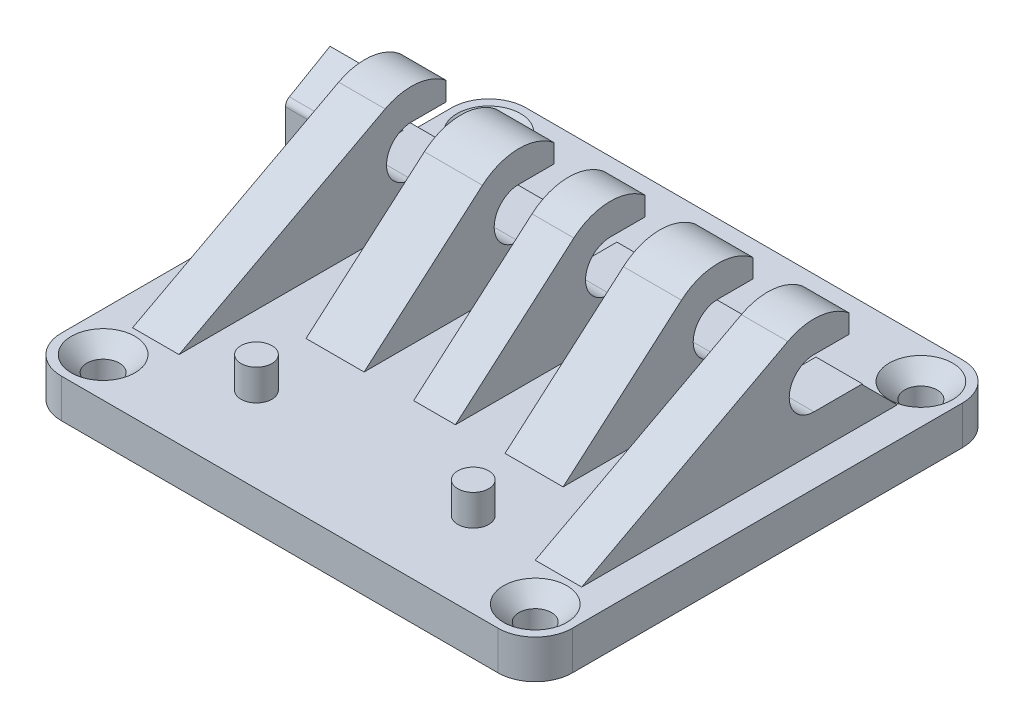
SolidWorks part; units mm, degrees
other "Markup1"
sketch "Sketch13" plane through (0, 20, 0) normal (-0.5335, 0.7333, 0.4215) x (0.8394, 0.3978, 0.3704)
sketch "Sketch14" plane through (0, 20, 0) normal (-0.5335, 0.7333, 0.4215) x (0.8394, 0.3978, 0.3704)
ref_plane "Front Plane" through (0, 0, 0) normal (0, 0, 1) x (1, 0, 0)
ref_plane "Top Plane" through (0, 0, 0) normal (0, 1, 0) x (1, 0, 0)
ref_plane "Right Plane" through (0, 0, 0) normal (1, 0, 0) x (0, 0, -1)
sketch "Sketch4" plane through (0, 0, 0) normal (0, 1, 0) x (1, 0, 0)
  line L0 (33, 60) -> (33, 0) construction
  line L1 (0, 0) -> (66, 0)
  line L2 (0, 0) -> (0, 60)
  line L3 (0, 60) -> (66, 60)
  line L4 (66, 0) -> (66, 60)
  line L6 (30.3, 20) -> (35.7, 20)
  line L7 (30.3, 20) -> (30.3, 60)
  line L8 (30.3, 60) -> (35.7, 60)
  line L9 (35.7, 20) -> (35.7, 60)
  line L10 (30.3, 20) -> (35.7, 60) construction
  line L11 (30.3, 60) -> (35.7, 20) construction
  line L12 (35.7, 60) -> (42.1, 60)
  line L13 (35.7, 60) -> (35.7, 20)
  line L14 (35.7, 20) -> (42.1, 20)
  line L15 (42.1, 60) -> (42.1, 20)
  line L16 (42.1, 20) -> (49.6, 20)
  line L17 (42.1, 20) -> (42.1, 60)
  line L18 (42.1, 60) -> (49.6, 60)
  line L19 (49.6, 20) -> (49.6, 60)
  line L20 (49.6, 60) -> (56, 60)
  line L21 (49.6, 60) -> (49.6, 20)
  line L22 (49.6, 20) -> (56, 20)
  line L23 (56, 60) -> (56, 20)
  line L24 (56, 50) -> (62, 50)
  line L25 (56, 50) -> (56, 10)
  line L26 (56, 10) -> (62, 10)
  line L27 (62, 50) -> (62, 10)
  point P7 (33, 40)
  point P22 (52.8, 20)
  dimension "D1" = 6
  dimension "D2" = 6.4
  dimension "D3" = 7.5
  dimension "D4" = 5.4
  dimension "D5" = 10
  dimension "D6" = 10
  dimension "D7" = 20
  dimension "D8" = 40
  dimension "D9" = 10
  dimension "D10" = 6.4
  dimension "D11" = 66
extrude "Boss-Extrude4" add sketch "Sketch4" along normal blind 5 contours L24 L27 L26 L25 L22 L16 L14 L6 L7 L3 L2 L1 L4 L23 | L15 L3 L9 L14 | L6 L9 L3 L7 | L16 L19 L3 L15 | L23 L3 L19 L22 | L27 L24 L23 L25 L26
sketch "Sketch6" plane through (0, 5, 0) normal (0, 1, 0) x (1, 0, 0)
  line L0 (42.1, 60) -> (49.6, 60) construction
  line L1 (49.6, 20) -> (49.6, 60) construction
  line L2 (49.6, 60) -> (56, 60) construction
  line L3 (56, 60) -> (56, 20) construction
  line L4 (66, 0) -> (66, 60)
  line L5 (66, 60) -> (0, 60)
  line L6 (0, 60) -> (0, 0)
  line L7 (0, 0) -> (66, 0)
  line L8 (66, 0) -> (66, 60)
  line L9 (66, 60) -> (0, 60)
  line L10 (0, 60) -> (0, 0)
  line L11 (0, 0) -> (66, 0)
  line L12 (49.6, 20) -> (56, 20) construction
  line L13 (49.6, 60) -> (49.6, 20) construction
  line L14 (42.1, 20) -> (49.6, 20) construction
  line L15 (35.7, 20) -> (42.1, 20) construction
  line L16 (42.1, 60) -> (42.1, 20) construction
  line L17 (42.1, 20) -> (42.1, 60) construction
  line L18 (35.7, 60) -> (42.1, 60) construction
  line L19 (30.3, 20) -> (35.7, 20) construction
  line L20 (30.3, 20) -> (30.3, 60) construction
  line L21 (30.3, 60) -> (35.7, 60) construction
  line L22 (35.7, 20) -> (35.7, 60) construction
  line L23 (35.7, 60) -> (35.7, 20) construction
  line L24 (0, 0) -> (66, 0) construction
  line L25 (66, 0) -> (66, 60) construction
  line L26 (0, 60) -> (66, 60) construction
  line L27 (0, 0) -> (0, 60) construction
  line L28 (56, 50) -> (62, 50) construction
  line L29 (62, 50) -> (62, 10) construction
  line L30 (56, 10) -> (62, 10) construction
  line L31 (56, 50) -> (56, 10) construction
  line L32 (42.1, 60) -> (49.6, 60)
  line L33 (49.6, 20) -> (49.6, 60)
  line L34 (49.6, 60) -> (56, 60)
  line L35 (56, 60) -> (56, 20)
  line L36 (49.6, 20) -> (56, 20)
  line L37 (49.6, 60) -> (49.6, 20)
  line L38 (42.1, 20) -> (49.6, 20)
  line L39 (35.7, 20) -> (42.1, 20)
  line L40 (42.1, 60) -> (42.1, 20)
  line L41 (42.1, 20) -> (42.1, 60)
  line L42 (35.7, 60) -> (42.1, 60)
  line L43 (30.3, 20) -> (35.7, 20)
  line L44 (30.3, 20) -> (30.3, 60)
  line L45 (30.3, 60) -> (35.7, 60)
  line L46 (35.7, 20) -> (35.7, 60)
  line L47 (35.7, 60) -> (35.7, 20)
  line L48 (0, 0) -> (66, 0)
  line L49 (66, 0) -> (66, 60)
  line L50 (0, 60) -> (66, 60)
  line L51 (0, 0) -> (0, 60)
  line L52 (56, 50) -> (62, 50)
  line L53 (62, 50) -> (62, 10)
  line L54 (56, 10) -> (62, 10)
  line L55 (56, 50) -> (56, 10)
  dimension "D1" = 0
extrude "Boss-Extrude5" add sketch "Sketch6" along normal blind 15 contours L43 L46 L9 L44 | L9 L40 L38 L33 | L35 L55 L54 L53 L52
sketch "Sketch7" plane through (30.3, 0, 0) normal (-1, 0, 0) x (0, 0, 1)
  line L0 (-40, 20) -> (-40, 5) construction
  line L1 (-20, 20) -> (-60, 20) construction
  line L2 (-20, 5) -> (-60, 5) construction
  circle A0 centre (-40, 12.8) radius 3.2
  point P8 (-40, 16)
  dimension "D1" = 6.4
  dimension "D2" = 4
extrude "Cut-Extrude2" cut sketch "Sketch7" against normal through all
sketch "Sketch8" plane through (30.3, 0, 0) normal (-1, 0, 0) x (0, 0, 1)
  line L0 (-20, 5) -> (-35.2856, 18.2419)
  line L1 (-40, 21) -> (-40, 5) construction
  line L2 (-60, 5) -> (-44.7144, 18.2419)
  line L4 (-60, 5) -> (-20, 5)
  line L5 (-20, 5) -> (-20, 20)
  line L6 (-20, 20) -> (-60, 20)
  line L7 (-60, 20) -> (-60, 5)
  line L8 (-60, 5) -> (-20, 5)
  line L9 (-20, 5) -> (-20, 20)
  line L10 (-20, 20) -> (-60, 20)
  line L11 (-60, 20) -> (-60, 5)
  circle A0 centre (-40, 12.8) radius 3.2 construction
  circle A1 centre (-40, 12.8) radius 3.2
  arc A2 (-44.7144, 18.2419) -> (-35.2856, 18.2419) centre (-40, 12.8) cw
  line M10 (-20, 5) -> (-20, 20)
  line M11 (-20, 20) -> (-60, 20)
  line M12 (-60, 20) -> (-60, 5)
  dimension "D1" = 0
extrude "Cut-Extrude3" cut sketch "Sketch8" against normal up to surface (19.3 mm away) contours L2 A2 L10 M12 | A2 L0 M11 M10 up to face at (49.6, 12.8, -36.8)
sketch "Sketch9" plane through (62, 0, 0) normal (1, 0, 0) x (0, 0, -1)
  line L0 (46.8685, 14.9596) -> (50, 5)
  line L1 (10, 5) -> (36.6192, 19.1569)
  line L4 (10, 5) -> (50, 5)
  line L5 (50, 5) -> (50, 20)
  line L6 (50, 20) -> (10, 20)
  line L7 (10, 20) -> (10, 5)
  line L8 (10, 5) -> (50, 5)
  line L9 (50, 5) -> (50, 20)
  line L10 (50, 20) -> (10, 20)
  line L11 (10, 20) -> (10, 5)
  circle A0 centre (40, 12.8) radius 3.2 construction
  circle A1 centre (40, 12.8) radius 3.2
  arc A2 (40, 20) -> (46.8685, 14.9596) centre (40, 12.8) cw
  arc A3 (40, 20) -> (36.6192, 19.1569) centre (40, 12.8) ccw
  line M9 (50, 5) -> (50, 20)
  line M10 (50, 20) -> (10, 20)
  line M11 (10, 20) -> (10, 5)
  dimension "D1" = 0
extrude "Cut-Extrude4" cut sketch "Sketch9" against normal up to next contours A3 L10 L1 M11 | A2 L0 M10 M9
ref_plane "Plane1" through (33, 0, 0) normal (-1, 0, 0) x (0, 0, 1)
mirror "Mirror1" about plane through (33, 0, 0) normal (-1, 0, 0) of "Cut-Extrude4", "Cut-Extrude3", "Cut-Extrude2", "Boss-Extrude5"
sketch "Sketch10" plane through (0, 5, 0) normal (0, 1, 0) x (1, 0, 0)
  line L0 (33, 60) -> (33, 0) construction
  line L1 (60.9, 5.1) -> (5.1, 5.1) construction
  line L2 (60.9, 5.1) -> (60.9, 54.9) construction
  line L3 (60.9, 54.9) -> (5.1, 54.9) construction
  line L4 (5.1, 5.1) -> (5.1, 54.9) construction
  line L5 (60.9, 5.1) -> (5.1, 54.9) construction
  line L6 (60.9, 54.9) -> (5.1, 5.1) construction
  line L9 (0, 60) -> (66, 60) construction
  line L10 (0, 0) -> (0, 60) construction
  circle A0 centre (5.1, 54.9) radius 2.1
  circle A1 centre (60.9, 54.9) radius 2.1
  circle A2 centre (60.9, 5.1) radius 2.1
  circle A3 centre (5.1, 5.1) radius 2.1
  point P0 (33, 30)
  point P9 (5.1, 57)
  point P10 (3, 54.9)
  dimension "D3" = 4.2
  dimension "D1" = 3
  dimension "D2" = 3
extrude "Cut-Extrude5" cut sketch "Sketch10" against normal up to next
chamfer "Chamfer1" distance 2 angle 45 4 edges at (5.1, 5, -3) (60.9, 5, -3) (60.9, 5, -52.8) (5.1, 5, -52.8)
fillet "Fillet1" radius 4.8 4 edges at (66, 2.5, 0) (0, 2.5, 0) (66, 2.5, -60) (0, 2.5, -60)
sketch "Sketch11" plane through (0, 5, 0) normal (0, 1, 0) x (1, 0, 0)
  line L1 (35.7, 36.8) -> (35.7, 43.2) construction
  line L2 (35.7, 36.8) -> (35.7, 43.2)
  line L3 (33, 11) -> (33, -11) construction
  circle A0 centre (47, 11) radius 2
  circle A1 centre (19, 11) radius 2
  point P4 (35.7, 40)
  dimension "D1" = 4
  dimension "D3" = 28
  dimension "D2" = 29
extrude "Boss-Extrude6" add sketch "Sketch11" along normal blind 4 contours A1 | A0
sketch "Sketch12" plane through (4, 0, 0) normal (-1, 0, 0) x (0, 0, 1)
  line L0 (-45.25, 15.8311) -> (-46.25, 15.8311)
  line L1 (-34.75, 15.8311) -> (-40, 18.8622)
  line L2 (-40, 18.8622) -> (-45.25, 15.8311)
  line L3 (-45.25, 15.8311) -> (-45.25, 9.7689)
  line L4 (-45.25, 9.7689) -> (-40, 6.7378)
  line L5 (-40, 6.7378) -> (-34.75, 9.7689)
  line L6 (-34.75, 9.7689) -> (-34.75, 15.8311)
  line L7 (-46.25, 15.8311) -> (-46.25, 5)
  line L8 (-50, 5) -> (-10, 5) construction
  line L9 (-34.75, 15.8311) -> (-33.75, 15.8311)
  line L10 (-33.75, 15.8311) -> (-33.75, 5)
  line L11 (-46.25, 5) -> (-33.75, 5)
  line L12 (-46.25, 15.8311) -> (-45.25, 15.8311)
  line L13 (-34.75, 15.8311) -> (-33.75, 15.8311)
  line L14 (-40, 18.8622) -> (-34.75, 15.8311)
  line L15 (-40, 18.8622) -> (-39.5, 19.7282)
  line L16 (-34.75, 15.8311) -> (-34.25, 16.6971)
  line L17 (-39.5, 19.7282) -> (-34.25, 16.6971)
  line L18 (-46.25, 9.6) -> (-44.9574, 9.6)
  line L19 (-40, 9.6) -> (-54.6901, 9.6) construction
  line L20 (-44.7144, 18.2419) -> (-60, 5) construction
  circle A0 centre (-40, 12.8) radius 3.2 construction
  circle A1 centre (-40, 12.8) radius 3.2
  circle A2 centre (-40, 12.8) radius 5.25 construction
  arc A3 (-34.25, 16.6971) -> (-33.75, 15.8311) centre (-34.75, 15.8311) cw
  line M12 (-50, 5) -> (-10, 5)
  dimension "D1" = 10.5
  dimension "D2" = 1
extrude "Boss-Extrude7" add sketch "Sketch12" along normal up to surface (4 mm away) contours L10 L9 L6 L5 L4 L3 L0 L7 M12 | A3 L16 L9 | L17 L15 L1 L16
sketch "Sketch15" plane through (4, 0, 0) normal (-1, 0, 0) x (0, 0, 1)
  line L0 (-40, 16) -> (-47.3023, 16)
  line L1 (-40, 9.6) -> (-54.6901, 9.6)
  line L2 (-44.5, 16) -> (-44.5, 18.4205)
  line L3 (-20, 5) -> (-35.2856, 18.2419)
  line L4 (-44.7144, 18.2419) -> (-60, 5)
  line L5 (-60, 5) -> (-20, 5)
  line L6 (-20, 5) -> (-35.2856, 18.2419)
  line L7 (-44.7144, 18.2419) -> (-60, 5)
  line L8 (-60, 5) -> (-20, 5)
  line L22 (-55.2, 0) -> (-4.8, 0)
  line L23 (-4.8, 0) -> (-4.8, 5)
  line L24 (-4.8, 5) -> (-33.75, 5)
  line L25 (-33.75, 5) -> (-33.75, 15.8311)
  line L26 (-34.25, 16.6971) -> (-39.5, 19.7282)
  line L27 (-39.5, 19.7282) -> (-40, 18.8622)
  line L28 (-40, 18.8622) -> (-34.75, 15.8311)
  line L29 (-34.75, 15.8311) -> (-34.75, 9.7689)
  line L30 (-34.75, 9.7689) -> (-40, 6.7378)
  line L31 (-40, 6.7378) -> (-44.9574, 9.6)
  line L32 (-44.9574, 9.6) -> (-46.25, 9.6)
  line L33 (-46.25, 9.6) -> (-46.25, 5)
  line L34 (-46.25, 5) -> (-55.2, 5)
  line L35 (-55.2, 5) -> (-55.2, 0)
  line L36 (-55.2, 0) -> (-4.8, 0)
  line L37 (-4.8, 0) -> (-4.8, 5)
  line L38 (-4.8, 5) -> (-33.75, 5)
  line L39 (-33.75, 5) -> (-33.75, 15.8311)
  line L40 (-34.25, 16.6971) -> (-39.5, 19.7282)
  line L41 (-39.5, 19.7282) -> (-40, 18.8622)
  line L42 (-40, 18.8622) -> (-34.75, 15.8311)
  line L43 (-34.75, 15.8311) -> (-34.75, 9.7689)
  line L44 (-34.75, 9.7689) -> (-40, 6.7378)
  line L45 (-40, 6.7378) -> (-44.9574, 9.6)
  line L46 (-44.9574, 9.6) -> (-46.25, 9.6)
  line L47 (-46.25, 9.6) -> (-46.25, 5)
  line L48 (-46.25, 5) -> (-55.2, 5)
  line L49 (-55.2, 5) -> (-55.2, 0)
  circle A0 centre (-40, 12.8) radius 3.2 construction
  circle A1 centre (-40, 12.8) radius 3.2
  arc A3 (-35.2856, 18.2419) -> (-44.7144, 18.2419) centre (-40, 12.8) ccw
  arc A4 (-35.2856, 18.2419) -> (-44.7144, 18.2419) centre (-40, 12.8) ccw
  arc A5 (-33.75, 15.8311) -> (-34.25, 16.6971) centre (-34.75, 15.8311) ccw
  arc A6 (-33.75, 15.8311) -> (-34.25, 16.6971) centre (-34.75, 15.8311) ccw
  arc M10 (-36.6192, 19.1569) -> (-46.8685, 14.9596) centre (-40, 12.8) ccw
  line M11 (-46.8685, 14.9596) -> (-50, 5)
  line M12 (-50, 5) -> (-46.25, 5)
  line M13 (-46.25, 5) -> (-46.25, 9.6)
  line M14 (-46.25, 9.6) -> (-44.9574, 9.6)
  circle M21 centre (-40, 12.8) radius 3.2
  dimension "D3" = 4.5
  dimension "D1" = 0
  dimension "D2" = 0
extrude "Cut-Extrude6" cut sketch "Sketch15" against normal through all contours L1 L0 M21 M10 M11 M14 | L0 L7 L1 M11 M10 | L7 L8 L1 M11 | L1 M13 M11 M12 | L0 L2 M10 | L7 L0 M10
chamfer "Chamfer2" distance 4.5 angle 45 5 edges at (5, 5, -46.25) (33, 5, -46.25) (45.85, 5, -46.25) (20.15, 5, -46.25) (59, 5, -46.25)
